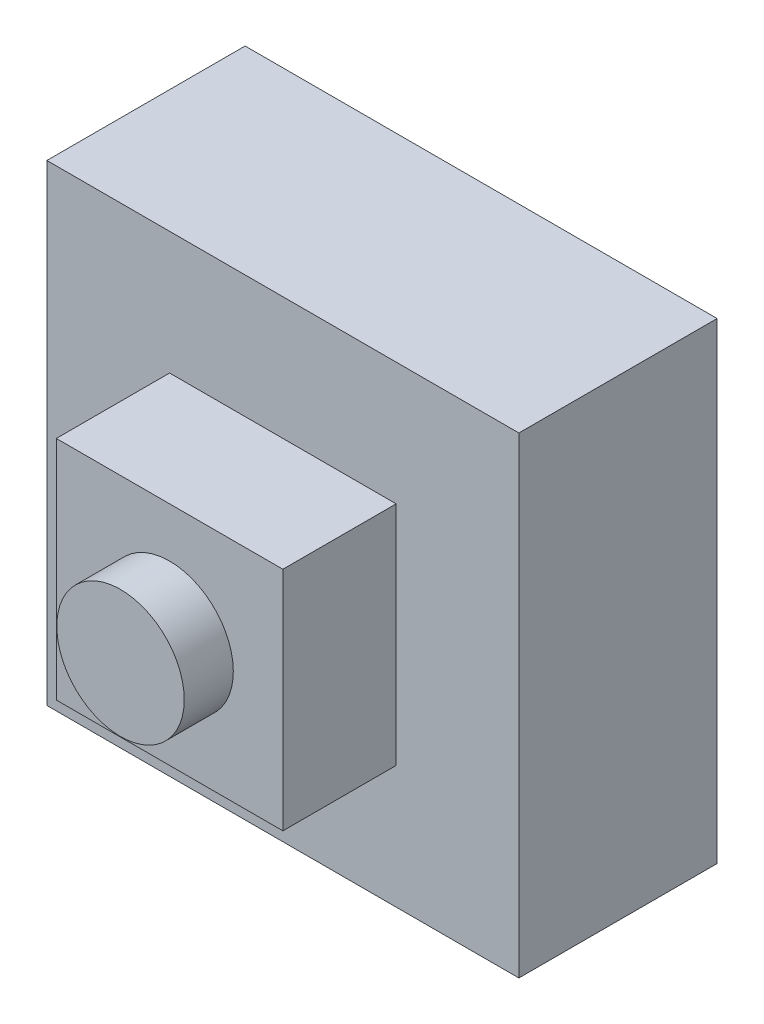
SolidWorks part; units mm, degrees
ref_plane "Front Plane" through (0, 0, 0) normal (0, 0, 1) x (1, 0, 0)
ref_plane "Top Plane" through (0, 0, 0) normal (0, 1, 0) x (1, 0, 0)
ref_plane "Right Plane" through (0, 0, 0) normal (1, 0, 0) x (0, 0, -1)
sketch "Sketch3" plane through (0, 0, 0) normal (0, 0, 1) x (1, 0, 0)
  line L1 (-3.048, -3.048) -> (3.048, -3.048)
  line L2 (-3.048, -3.048) -> (-3.048, 3.048)
  line L3 (-3.048, 3.048) -> (3.048, 3.048)
  line L4 (3.048, -3.048) -> (3.048, 3.048)
  line L5 (-3.048, -3.048) -> (3.048, 3.048) construction
  line L6 (-3.048, 3.048) -> (3.048, -3.048) construction
  point P0 (0, 0)
  dimension "D1" = 6.096
  dimension "D2" = 6.096
extrude "Boss-Extrude1" add sketch "Sketch3" along normal mid plane 11.43
sketch "Sketch4" plane through (0, 0, 5.715) normal (0, 0, 1) x (1, 0, 0)
  circle A0 centre (0, 0) radius 1.7145
extrude "Boss-Extrude2" add sketch "Sketch4" along normal blind 1.3208
mirror "Mirror1" about plane through (0, 0, 0) normal (0, 0, 1) of "Boss-Extrude2"
sketch "Sketch5" plane through (0, 0, 0) normal (0, 0, 1) x (1, 0, 0)
  line L1 (-6.35, -6.35) -> (6.35, -6.35)
  line L2 (-6.35, -6.35) -> (-6.35, 6.35)
  line L3 (-6.35, 6.35) -> (6.35, 6.35)
  line L4 (6.35, -6.35) -> (6.35, 6.35)
  line L5 (-6.35, -6.35) -> (6.35, 6.35) construction
  line L6 (-6.35, 6.35) -> (6.35, -6.35) construction
  point P0 (0, 0)
  dimension "D1" = 12.7
  dimension "D2" = 12.7
extrude "Boss-Extrude4" add sketch "Sketch5" along normal mid plane 5.334
